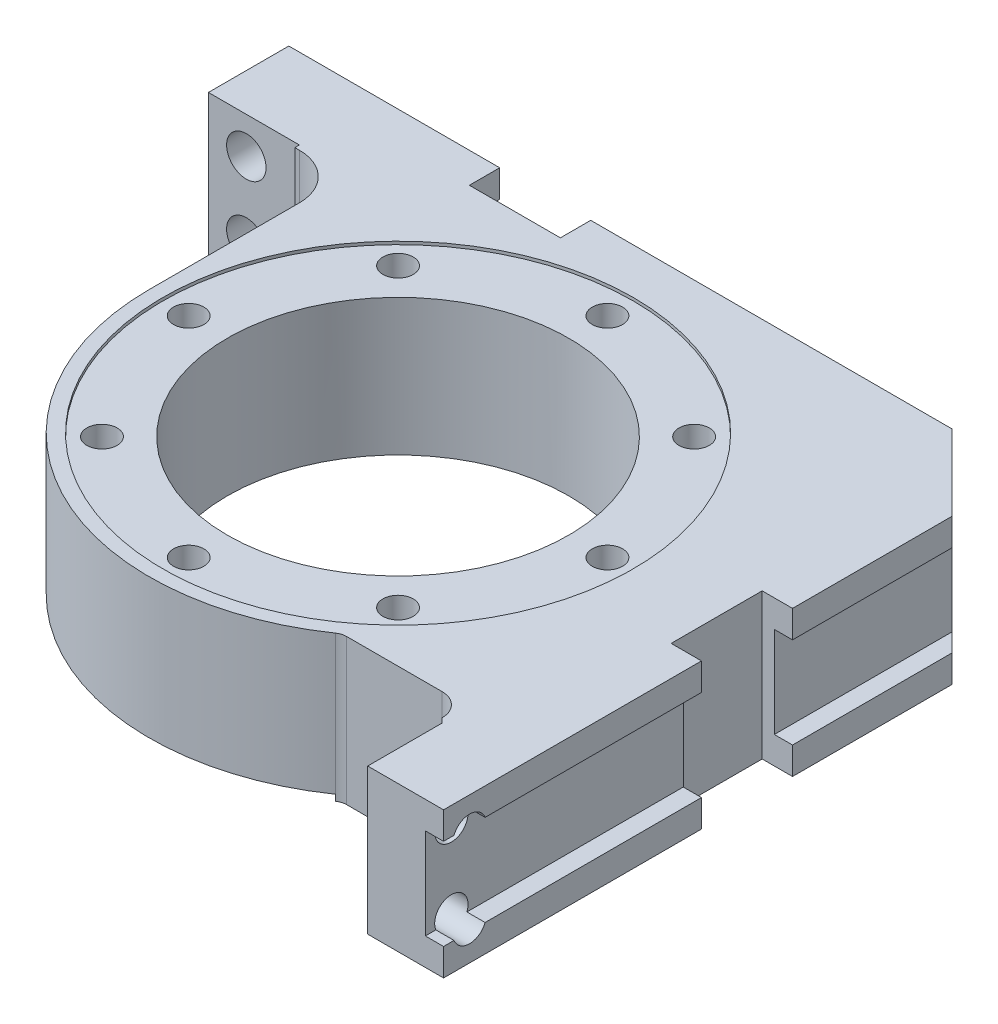
SolidWorks part; units mm, degrees
ref_plane "Front Plane" through (0, 0, 0) normal (0, 0, 1) x (1, 0, 0)
ref_plane "Top Plane" through (0, 0, 0) normal (0, 1, 0) x (1, 0, 0)
ref_plane "Right Plane" through (0, 0, 0) normal (1, 0, 0) x (0, 0, -1)
sketch "Sketch1" plane through (0, 0, 0) normal (0, 1, 0) x (1, 0, 0)
  line L0 (-235.1915, 101.7592) -> (-96.1915, 101.7592)
  line L1 (-235.1915, 101.7592) -> (-96.1915, 101.7592)
  line L2 (-235.1915, 101.7592) -> (-235.1915, 45.7592)
  line L3 (201.8085, -283.2408) -> (251.8085, -283.2408)
  line L4 (251.8085, 101.7592) -> (251.8085, -53.2408)
  line L5 (-235.1915, 101.7592) -> (-96.1915, 101.7592)
  line L6 (-235.1915, 101.7592) -> (-235.1915, 45.7592)
  line L7 (-175.1915, 45.7592) -> (-172.1915, 45.7592)
  line L8 (251.8085, 101.7592) -> (251.8085, 45.7592)
  line L13 (251.8085, -283.2408) -> (201.8085, -283.2408)
  line L14 (251.8085, -283.2408) -> (251.8085, -113.2408)
  line L17 (-36.1915, 101.7592) -> (251.8085, 101.7592)
  line L19 (-96.1915, 101.7592) -> (-96.1915, 81.7592)
  line L20 (-96.1915, 81.7592) -> (-36.1915, 81.7592)
  line L21 (-36.1915, 101.7592) -> (-36.1915, 81.7592)
  line L22 (-36.1915, 101.7592) -> (251.8085, 101.7592)
  line L23 (251.8085, -283.2408) -> (201.8085, -283.2408)
  line L24 (-142.1915, -83.2408) -> (-142.1915, 15.7592)
  line L25 (251.8085, -283.2408) -> (251.8085, -113.2408)
  line L26 (251.8085, -113.2408) -> (251.8085, -283.2408)
  line L27 (251.8085, -113.2408) -> (231.8085, -113.2408)
  line L29 (251.8085, -53.2408) -> (231.8085, -53.2408)
  line L30 (231.8085, -113.2408) -> (231.8085, -53.2408)
  line L31 (-235.1915, 101.7592) -> (-235.1915, 48.7592)
  line L32 (-235.1915, 48.7592) -> (-175.1915, 48.7592)
  line L33 (-175.1915, 48.7592) -> (-175.1915, 45.7592)
  line L36 (251.8085, -283.2408) -> (201.8085, -283.2408)
  line L38 (201.8085, -234.2408) -> (201.8085, -283.2408)
  line L39 (198.8085, -231.2408) -> (201.8085, -234.2408)
  line L41 (183.8085, -216.2408) -> (117.7616, -216.2408)
  circle A0 centre (21.8085, -83.2408) radius 164
  arc A1 (-172.1915, 45.7592) -> (-142.1915, 15.7592) centre (-172.1915, 15.7592) cw
  arc A2 (198.8085, -231.2408) -> (183.8085, -216.2408) centre (183.8085, -231.2408) ccw
  dimension "D6" = 328
  dimension "D9" = 30
  dimension "D1" = 487
  dimension "D2" = 385
  dimension "D3" = 56
  dimension "D4" = 139
  dimension "D5" = 20
  dimension "D7" = 60
  dimension "D8" = 60
  dimension "D10" = 170
  dimension "D11" = 60
  dimension "D12" = 20
  dimension "D13" = 53
  dimension "D14" = 50
  dimension "D15" = 15
extrude "Boss-Extrude1" add sketch "Sketch1" along normal blind 96 contours A2 L39 L38 L3 L14 L27 L30 L29 L4 L17 L21 L20 L19 L0 L2 L32 L33 L7 A1 L24 A0 L41
sketch "Sketch2" plane through (0, 96, 0) normal (0, 1, 0) x (1, 0, 0)
  circle A0 centre (21.8085, -83.2408) radius 164
  circle A1 centre (21.8085, -83.2408) radius 112.5
  dimension "D1" = 225
extrude "Boss-Extrude2" add sketch "Sketch2" against normal blind 96
sketch "Sketch3" plane through (0, 96, 0) normal (0, 1, 0) x (1, 0, 0)
  circle A0 centre (21.8085, -83.2408) radius 138
  circle A1 centre (21.8085, 54.7592) radius 10
  dimension "D1" = 276
  dimension "D2" = 20
extrude "Cut-Extrude2" cut sketch "Sketch3" against normal blind 22 contours A1
pattern_circular "CirPattern1" count 8 over 360 about axis through (21.8085, 0, 83.2408) along (0, 1, 0) of "Cut-Extrude2"
sketch "Sketch4" plane through (0, 0, 0) normal (0, -1, 0) x (-1, 0, 0)
  circle A0 centre (-21.8085, -83.2408) radius 135
  circle A1 centre (-20.8648, -218.2375) radius 8
  dimension "D1" = 270
  dimension "D2" = 16
extrude "Cut-Extrude3" cut sketch "Sketch4" against normal blind 26 contours A1
pattern_circular "CirPattern2" count 8 over 360 about axis through (21.8085, 0, 83.2408) along (0, 1, 0) of "Cut-Extrude3"
fillet "Fillet1" radius 10 1 edges at (117.7616, 48, 216.2408)
sketch "Sketch5" plane through (0, 96, 0) normal (0, 1, 0) x (1, 0, 0)
  line L0 (201.8085, 101.7592) -> (251.8085, 51.7592)
  line L1 (251.8085, 101.7592) -> (201.8085, 101.7592)
  line L2 (251.8085, 101.7592) -> (251.8085, 51.7592)
  line L3 (251.8085, 51.7592) -> (201.8085, 51.7592)
  line L4 (201.8085, 101.7592) -> (201.8085, 51.7592)
  line M21 (251.8085, -53.2408) -> (251.8085, 101.7592)
  line M22 (251.8085, 101.7592) -> (-36.1915, 101.7592)
  dimension "D1" = 50
  dimension "D2" = 50
extrude "Cut-Extrude4" cut sketch "Sketch5" against normal through all both and the other way through all contours L0 M22 M21
sketch "Sketch6" plane through (0, 96, 0) normal (0, 1, 0) x (1, 0, 0)
  circle A0 centre (21.8085, -83.2408) radius 155
  dimension "D1" = 310
extrude "Cut-Extrude5" cut sketch "Sketch6" against normal blind 2 and the other way through all
sketch "Sketch7" plane through (0, 0, 0) normal (0, -1, 0) x (1, 0, 0)
  circle A0 centre (21.8085, 83.2408) radius 164
  dimension "D1" = 328
extrude "Cut-Extrude6" cut sketch "Sketch7" against normal blind 4
sketch "Sketch8" plane through (0, 0, 0) normal (1, 0, 0) x (0, 0, -1)
  line L0 (101.7592, 0) -> (101.7592, 96) construction
  line L1 (89.7592, 18) -> (113.7592, 18)
  line L2 (89.7592, 18) -> (89.7592, 78)
  line L3 (89.7592, 78) -> (113.7592, 78)
  line L4 (113.7592, 18) -> (113.7592, 78)
  line L5 (89.7592, 18) -> (113.7592, 78) construction
  line L6 (89.7592, 78) -> (113.7592, 18) construction
  point P0 (101.7592, 48)
  dimension "D1" = 60
  dimension "D2" = 24
extrude "Cut-Extrude7" cut sketch "Sketch8" against normal through all both and the other way through all
sketch "Sketch9" plane through (0, 0, 283.2408) normal (0, 0, 1) x (1, 0, 0)
  line L0 (251.8085, 96) -> (251.8085, 0) construction
  line L1 (239.8085, 18) -> (263.8085, 18)
  line L2 (239.8085, 18) -> (239.8085, 78)
  line L3 (239.8085, 78) -> (263.8085, 78)
  line L4 (263.8085, 18) -> (263.8085, 78)
  line L5 (239.8085, 18) -> (263.8085, 78) construction
  line L6 (239.8085, 78) -> (263.8085, 18) construction
  point P0 (251.8085, 48)
  dimension "D1" = 24
  dimension "D2" = 60
extrude "Cut-Extrude8" cut sketch "Sketch9" against normal through all both and the other way through all
sketch "Sketch10" plane through (201.8085, 0, 0) normal (-1, 0, 0) x (0, 0, 1)
  line L0 (283.2408, 96) -> (283.2408, 0) construction
  line L1 (266.1008, 22) -> (300.3809, 22)
  line L2 (266.1008, 22) -> (266.1008, 74)
  line L3 (266.1008, 74) -> (300.3809, 74)
  line L4 (300.3809, 22) -> (300.3809, 74)
  line L5 (266.1008, 22) -> (300.3809, 74) construction
  line L6 (266.1008, 74) -> (300.3809, 22) construction
  circle A0 centre (266.1008, 74) radius 11
  circle A1 centre (266.1008, 22) radius 11
  point P0 (283.2408, 48)
  dimension "D2" = 22
  dimension "D3" = 22
  dimension "D1" = 52
extrude "Cut-Extrude9" cut sketch "Sketch10" against normal through all both and the other way through all contours L2 A1 L1 | L1 A1 L2 | A0
sketch "Sketch11" plane through (0, 0, -48.7592) normal (0, 0, 1) x (1, 0, 0)
  line L0 (-235.1915, 96) -> (-235.1915, 0) construction
  line L1 (-260.1915, 24) -> (-210.1915, 24)
  line L2 (-260.1915, 24) -> (-260.1915, 72)
  line L3 (-260.1915, 72) -> (-210.1915, 72)
  line L4 (-210.1915, 24) -> (-210.1915, 72)
  line L5 (-260.1915, 24) -> (-210.1915, 72) construction
  line L6 (-260.1915, 72) -> (-210.1915, 24) construction
  circle A0 centre (-210.1915, 72) radius 13
  circle A1 centre (-210.1915, 24) radius 13
  point P0 (-235.1915, 48)
  dimension "D3" = 26
  dimension "D4" = 26
  dimension "D1" = 48
  dimension "D2" = 50
extrude "Cut-Extrude10" cut sketch "Sketch11" against normal through all both and the other way through all contours A0 | A1
